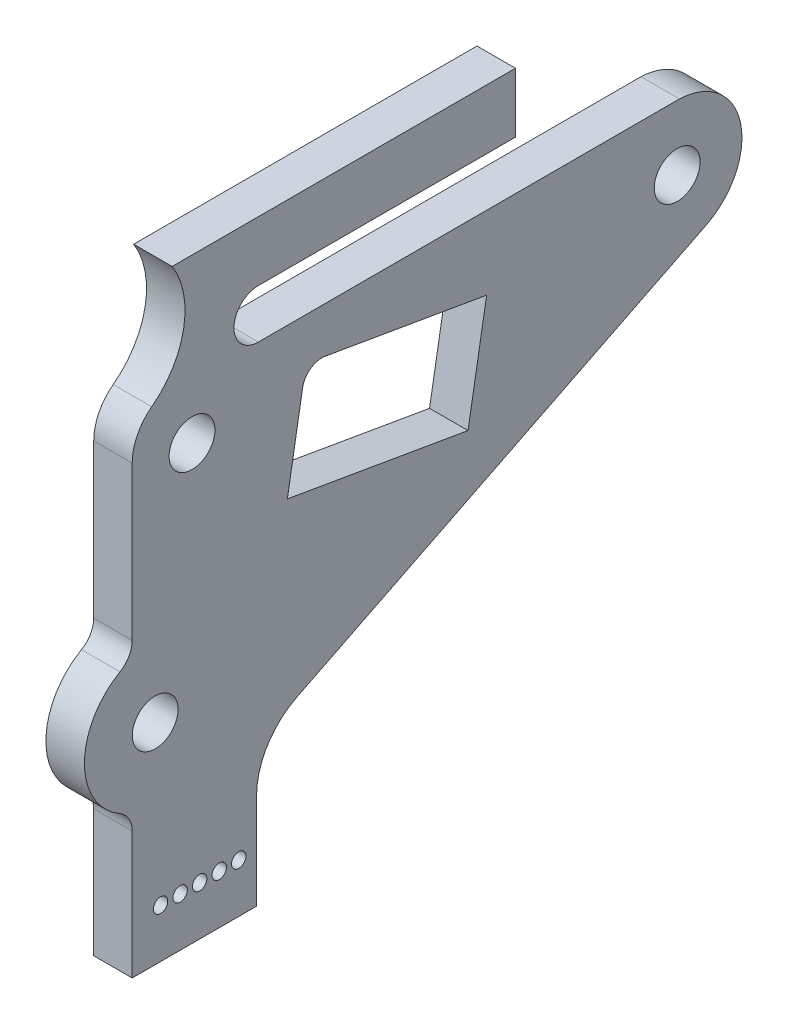
SolidWorks part; units mm, degrees
material "Hardboard"
ref_plane "Front Plane" through (0, 0, 0) normal (0, 0, 1) x (1, 0, 0)
ref_plane "Top Plane" through (0, 0, 0) normal (0, 1, 0) x (1, 0, 0)
ref_plane "Right Plane" through (0, 0, 0) normal (1, 0, 0) x (0, 0, -1)
sketch "Sketch1" plane through (0, 0, 0) normal (1, 0, 0) x (0, 0, -1)
  line L0 (-56.6254, 5.3138) -> (-52.4758, 5.3138) construction
  line L1 (-56.6254, 2.387) -> (-56.6254, -13.5592)
  line L2 (-56.6254, -43.9437) -> (-43.7075, -43.9437)
  line L3 (-43.7075, -43.9437) -> (-43.7075, -34.0304)
  line L4 (-43.7075, -20.39) -> (-25.8088, -20.39) construction
  line L5 (6.73, -20.39) -> (6.73, 6.726) construction
  line L6 (0.2329, 6.726) -> (0, 0) construction
  line L7 (6.73, 0) -> (0, 0) construction
  line L8 (-36.5684, 1.976) -> (-19.7977, -0.9146)
  line L9 (-38.916, 0.3187) -> (-40.5041, -8.8947)
  line L10 (-19.7977, -0.9146) -> (-21.7309, -12.1305)
  line L11 (-40.5041, -8.8947) -> (-21.7309, -12.1305)
  line L12 (-45.5531, -38.8637) -> (-47.5851, -38.8637) construction
  line L13 (-43.5151, 11.806) -> (-16.804, 11.806)
  line L14 (-16.804, 11.806) -> (-16.804, 18.009)
  line L15 (-16.804, 18.009) -> (-52.4758, 18.009)
  line L16 (-52.4758, 18.009) -> (-52.4758, 5.3138) construction
  line L17 (-43.5151, 6.726) -> (0.2329, 6.726)
  line L18 (-42.8121, -7.8827) -> (-43.2653, 4.8092) construction
  line L19 (0.2329, 6.726) -> (6.73, 6.726) construction
  line L20 (-25.8088, -20.39) -> (6.73, -20.39) construction
  line L21 (-25.8088, -20.39) -> (3.0033, -6.0227)
  line L22 (-25.8088, -20.39) -> (-39.488, -27.2112)
  line L23 (-43.7075, -29.3153) -> (-43.7075, -20.39) construction
  line L24 (-56.6254, -15.1828) -> (-56.6254, -29.0916) construction
  line L25 (-56.6254, -30.7152) -> (-56.6254, -43.9437)
  circle A0 centre (0, 0) radius 2.3813
  circle A1 centre (-45.5531, -38.8637) radius 0.75
  circle A2 centre (-47.5851, -38.8637) radius 0.75
  circle A3 centre (-49.6171, -38.8637) radius 0.75
  circle A4 centre (-51.6491, -38.8637) radius 0.75
  circle A5 centre (-54.2362, -22.1372) radius 2.3812
  circle A6 centre (-50.4101, 1.0794) radius 2.3812
  circle A7 centre (-53.6811, -38.8637) radius 0.75
  arc A8 (-43.5151, 6.726) -> (-43.5151, 11.806) centre (-43.5151, 9.266) cw
  arc A9 (-52.4758, 18.009) -> (-54.597, 6.4483) centre (-59.8045, 13.3788) cw
  arc A10 (0.2329, 6.726) -> (3.0033, -6.0227) centre (0, 0) cw
  arc A11 (-43.7075, -34.0304) -> (-39.488, -27.2112) centre (-36.0875, -34.0304) cw
  arc A12 (-56.6254, 2.387) -> (-54.597, 6.4483) centre (-51.5454, 2.387) cw
  arc A13 (-57.8999, -15.7615) -> (-57.8999, -28.5129) centre (-54.2362, -22.1372) ccw
  arc A14 (-56.6254, -13.5592) -> (-57.8999, -15.7615) centre (-59.1654, -13.5592) cw
  arc A15 (-56.6254, -30.7152) -> (-57.8999, -28.5129) centre (-59.1654, -30.7152) ccw
  arc A16 (-38.916, 0.3187) -> (-36.5684, 1.976) centre (-36.9135, -0.0265) cw
  point P61 (-38.5709, 2.3212)
  dimension "D1" = 4.7625
  dimension "D2" = 1.5
  dimension "D9" = 7.62
  dimension "D10" = 5.08
  dimension "D11" = 2.54
  dimension "D12" = 2.54
  dimension "D13" = 2.032
  dimension "D3" = 5.08
  dimension "D5" = 2.032
  dimension "D6" = 19.05
  dimension "D7" = 6.203
  dimension "D8" = 5.08
  dimension "D4" = 5
extrude "Boss-Extrude1" add sketch "Sketch1" along normal mid plane 4
